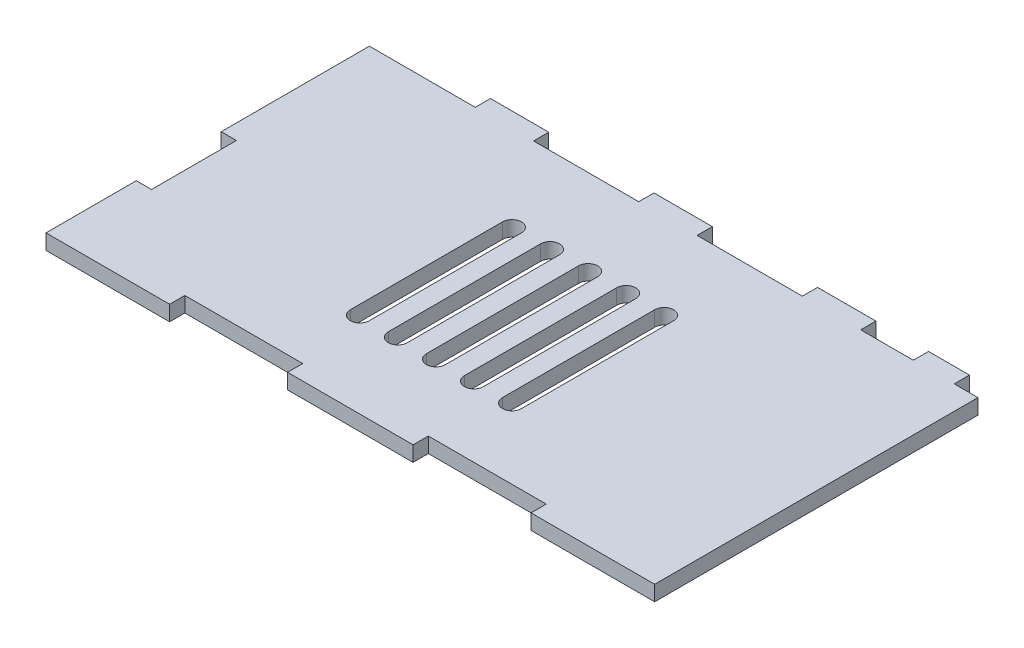
SolidWorks part; units mm, degrees
ref_plane "Front Plane" through (0, 0, 0) normal (0, 0, 1) x (1, 0, 0)
ref_plane "Top Plane" through (0, 0, 0) normal (0, 1, 0) x (1, 0, 0)
ref_plane "Right Plane" through (0, 0, 0) normal (1, 0, 0) x (0, 0, -1)
sketch "Sketch1" plane through (0, 0, 0) normal (0, 1, 0) x (1, 0, 0)
  line L1 (0, 0) -> (156, 0)
  line L2 (0, 0) -> (0, 85)
  line L3 (0, 85) -> (156, 85)
  line L4 (156, 0) -> (156, 85)
  dimension "D1" = 156
  dimension "D2" = 85
extrude "Boss-Extrude1" add sketch "Sketch1" along normal blind 4
sketch "Sketch2" plane through (0, 4, 0) normal (0, 1, 0) x (1, 0, 0)
  line L0 (156, 85) -> (0, 85) construction
  line L1 (23.83, 85) -> (39.16, 85)
  line L2 (23.83, 85) -> (23.83, 89)
  line L3 (23.83, 89) -> (39.16, 89)
  line L4 (39.16, 85) -> (39.16, 89)
  line L5 (0, 85) -> (0, 0) construction
  line L6 (66.83, 85) -> (66.83, 89)
  line L7 (66.83, 85) -> (82.16, 85)
  line L8 (82.16, 85) -> (82.16, 89)
  line L9 (66.83, 89) -> (82.16, 89)
  line L10 (109.83, 85) -> (109.83, 89)
  line L11 (109.83, 85) -> (125.16, 85)
  line L12 (125.16, 85) -> (125.16, 89)
  line L13 (109.83, 89) -> (125.16, 89)
  dimension "D1" = 23.83
  dimension "D2" = 15.33
  dimension "D3" = 4
  dimension "D4" = 3
extrude "Boss-Extrude2" add sketch "Sketch2" against normal blind 4
sketch "Sketch3" plane through (0, 4, 0) normal (0, 1, 0) x (1, 0, 0)
  line L0 (59.5, 0) -> (59.5, 4)
  line L1 (123.5, 0) -> (92.5, 0)
  line L2 (123.5, 0) -> (123.5, 4)
  line L3 (123.5, 4) -> (92.5, 4)
  line L4 (92.5, 0) -> (92.5, 4)
  line L5 (59.5, 0) -> (28.5, 0)
  line L6 (28.5, 0) -> (28.5, 4)
  line L7 (59.5, 4) -> (28.5, 4)
  line L12 (-4.5, 0) -> (-4.5, 4) [skipped]
  line L13 (-4.5, 0) -> (-35.5, 0) [skipped]
  line L14 (-35.5, 0) -> (-35.5, 4) [skipped]
  line L15 (-4.5, 4) -> (-35.5, 4) [skipped]
  line L16 (0, 0) -> (156, 0) construction
  dimension "D1" = 31
  dimension "D2" = 4
  dimension "D4" = 32.5
  dimension "D3" = 3
extrude "Cut-Extrude2" cut sketch "Sketch3" against normal blind 4
sketch "Sketch4" plane through (0, 4, 0) normal (0, 1, 0) x (1, 0, 0)
  line L0 (0, 85) -> (0, 0) construction
  line L1 (0, 0) -> (-4, 0)
  line L2 (0, 0) -> (0, 26.74)
  line L3 (0, 26.74) -> (-4, 26.74)
  line L4 (-4, 0) -> (-4, 26.74)
  line L5 (0, 47.98) -> (-4, 47.98)
  line L6 (0, 47.98) -> (0, 76.22)
  line L7 (0, 76.22) -> (-4, 76.22)
  line L8 (-4, 47.98) -> (-4, 76.22)
  dimension "D2" = 4
  dimension "D1" = 26.74
  dimension "D3" = 21.24
  dimension "D4" = 4
  dimension "D5" = 28.24
extrude "Boss-Extrude3" add sketch "Sketch4" against normal blind 4
sketch "Sketch5" plane through (0, 4, 0) normal (0, 1, 0) x (1, 0, 0)
  line L0 (156, 85) -> (125.16, 85) construction
  line L1 (149.75, 85) -> (139, 85)
  line L2 (149.75, 85) -> (149.75, 89)
  line L3 (149.75, 89) -> (139, 89)
  line L4 (139, 85) -> (139, 89)
  line L5 (156, 0) -> (156, 85) construction
  dimension "D1" = 6.25
  dimension "D2" = 10.75
  dimension "D3" = 4
extrude "Boss-Extrude4" add sketch "Sketch5" against normal blind 4
sketch "Sketch6" plane through (0, 4, 0) normal (0, 1, 0) x (1, 0, 0)
  line L0 (76, 22.5) -> (76, 62.5) construction
  line L1 (73.5, 22.5) -> (73.5, 62.5)
  line L2 (78.5, 22.5) -> (78.5, 62.5)
  line L3 (156, 0) -> (156, 85) construction
  line L4 (59.5, 0) -> (92.5, 0) construction
  line L5 (68.5, 22.5) -> (68.5, 62.5)
  line L6 (63.5, 22.5) -> (63.5, 62.5)
  line L7 (66, 22.5) -> (66, 62.5) construction
  line L8 (58.5, 22.5) -> (58.5, 62.5)
  line L9 (53.5, 22.5) -> (53.5, 62.5)
  line L10 (56, 22.5) -> (56, 62.5) construction
  line L11 (78.5, 22.5) -> (78.5, 62.5)
  line L12 (73.5, 22.5) -> (73.5, 62.5)
  line L13 (76, 22.5) -> (76, 62.5) construction
  line L14 (68.5, 22.5) -> (68.5, 62.5)
  line L15 (63.5, 22.5) -> (63.5, 62.5)
  line L16 (66, 22.5) -> (66, 62.5) construction
  line L17 (88.5, 22.5) -> (88.5, 62.5)
  line L18 (83.5, 22.5) -> (83.5, 62.5)
  line L19 (86, 22.5) -> (86, 62.5) construction
  line L20 (78.5, 22.5) -> (78.5, 62.5)
  line L21 (73.5, 22.5) -> (73.5, 62.5)
  line L22 (76, 22.5) -> (76, 62.5) construction
  line L23 (88.5, 22.5) -> (88.5, 62.5)
  line L24 (83.5, 22.5) -> (83.5, 62.5)
  line L25 (86, 22.5) -> (86, 62.5) construction
  line L26 (98.5, 22.5) -> (98.5, 62.5)
  line L27 (93.5, 22.5) -> (93.5, 62.5)
  line L28 (96, 22.5) -> (96, 62.5) construction
  arc A0 (73.5, 22.5) -> (78.5, 22.5) centre (76, 22.5) ccw
  arc A1 (78.5, 62.5) -> (73.5, 62.5) centre (76, 62.5) ccw
  arc A2 (63.5, 22.5) -> (68.5, 22.5) centre (66, 22.5) ccw
  arc A3 (68.5, 62.5) -> (63.5, 62.5) centre (66, 62.5) ccw
  arc A4 (53.5, 22.5) -> (58.5, 22.5) centre (56, 22.5) ccw
  arc A5 (58.5, 62.5) -> (53.5, 62.5) centre (56, 62.5) ccw
  arc A6 (73.5, 22.5) -> (78.5, 22.5) centre (76, 22.5) ccw
  arc A7 (78.5, 62.5) -> (73.5, 62.5) centre (76, 62.5) ccw
  arc A8 (63.5, 22.5) -> (68.5, 22.5) centre (66, 22.5) ccw
  arc A9 (68.5, 62.5) -> (63.5, 62.5) centre (66, 62.5) ccw
  arc A10 (83.5, 22.5) -> (88.5, 22.5) centre (86, 22.5) ccw
  arc A11 (88.5, 62.5) -> (83.5, 62.5) centre (86, 62.5) ccw
  arc A12 (73.5, 22.5) -> (78.5, 22.5) centre (76, 22.5) ccw
  arc A13 (78.5, 62.5) -> (73.5, 62.5) centre (76, 62.5) ccw
  arc A14 (83.5, 22.5) -> (88.5, 22.5) centre (86, 22.5) ccw
  arc A15 (88.5, 62.5) -> (83.5, 62.5) centre (86, 62.5) ccw
  arc A16 (93.5, 22.5) -> (98.5, 22.5) centre (96, 22.5) ccw
  arc A17 (98.5, 62.5) -> (93.5, 62.5) centre (96, 62.5) ccw
  point P2 (76, 42.5)
  point P9 (156, 42.5)
  point P14 (76, 0)
  point P18 (66, 42.5)
  point P25 (56, 42.5)
  point P32 (76, 42.5)
  point P39 (66, 42.5)
  point P46 (86, 42.5)
  point P53 (76, 42.5)
  point P60 (86, 42.5)
  point P67 (96, 42.5)
  dimension "D1" = 5
  dimension "D2" = 40
  dimension "D3" = 3
  dimension "D4" = 3
extrude "Cut-Extrude3" cut sketch "Sketch6" against normal blind 4 contours L5 A3 L6 A2 | L8 A5 L9 A4 | L2 A1 L1 A0 | L17 A11 L18 A10 | L26 A17 L27 A16
sketch "Sketch7" plane through (0, 4, 0) normal (0, 1, 0) x (1, 0, 0)
  line L1 (0, 85) -> (-4, 85)
  line L2 (0, 85) -> (0, 76.22)
  line L3 (0, 76.22) -> (-4, 76.22)
  line L4 (-4, 85) -> (-4, 76.22)
  line L5 (0, 47.98) -> (-4, 47.98)
  line L6 (0, 47.98) -> (0, 46.0568)
  line L7 (0, 46.0568) -> (-4, 46.0568)
  line L8 (-4, 47.98) -> (-4, 46.0568)
extrude "Boss-Extrude5" add sketch "Sketch7" against normal blind 4
sketch "Sketch8" plane through (0, 4, 0) normal (0, 1, 0) x (1, 0, 0)
  line L0 (0.5, 23.7401) -> (-3.5, 23.7401) construction
  line L1 (-4, 26.74) -> (0, 26.74)
  line L2 (-4, 26.74) -> (-4, 23.7401)
  line L3 (-4, 23.7401) -> (0, 23.7401)
  line L4 (0, 26.74) -> (0, 23.7401)
extrude "Cut-Extrude4" cut sketch "Sketch8" against normal blind 4
equation "\"Tolerantie\"= 0.5"
equation "\"D1@Sketch2\"=24.33-\"Tolerantie\""
equation "\"D2@Sketch2\"=14.33+2*\"Tolerantie\""
equation "\"D4@Sketch3\"=32+\"Tolerantie\""
equation "\"D1@Sketch3\"=32-2*\"Tolerantie\""
equation "\"D1@Sketch4\"=26.24+\"Tolerantie\""
equation "\"D3@Sketch4\"=22.24-2*\"Tolerantie\""
equation "\"D5@Sketch4\"=27.24+2*\"Tolerantie\""
